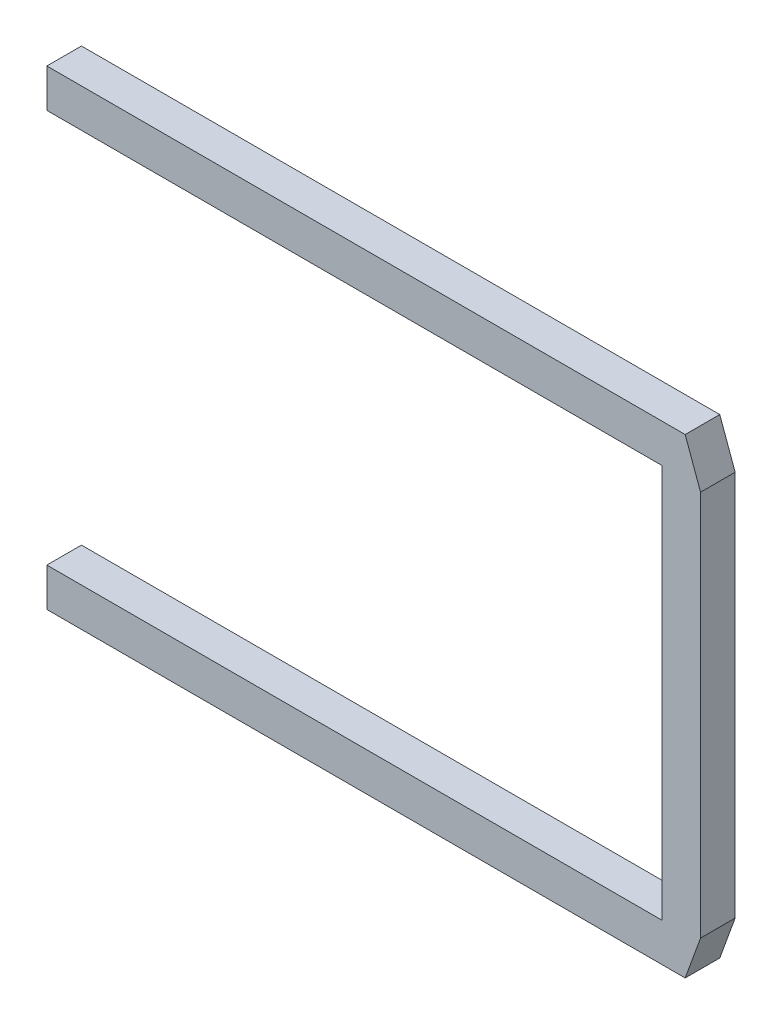
SolidWorks part; units mm, degrees
ref_plane "Front Plane" through (0, 0, 0) normal (0, 0, 1) x (1, 0, 0)
ref_plane "Top Plane" through (0, 0, 0) normal (0, 1, 0) x (1, 0, 0)
ref_plane "Right Plane" through (0, 0, 0) normal (1, 0, 0) x (0, 0, -1)
sketch "Sketch1" plane through (0, 0, 0) normal (0, 0, 1) x (1, 0, 0)
  line L0 (-42.5, -25.6) -> (-42.5, -30.6)
  line L1 (-42.5, 30.6) -> (42.5, 30.6)
  line L2 (-42.5, 30.6) -> (-42.5, 25.6)
  line L3 (-42.5, -30.6) -> (42.5, -30.6)
  line L4 (42.5, 30.6) -> (42.5, -30.6)
  line L5 (-42.5, 30.6) -> (42.5, -30.6) construction
  line L6 (-42.5, -30.6) -> (42.5, 30.6) construction
  line L7 (-42.5, 25.6) -> (37.5, 25.6)
  line L9 (-42.5, -25.6) -> (37.5, -25.6)
  line L10 (37.5, 25.6) -> (37.5, -25.6)
  point P0 (0, 0)
  dimension "D1" = 5
  dimension "D2" = 5
  dimension "D3" = 5
  dimension "D4" = 80
  dimension "D5" = 51.2
extrude "Boss-Extrude1" add sketch "Sketch1" along normal blind 4.5
chamfer "Chamfer1" distance 2 angle 70 2 edges at (42.5, -30.6, 2.25) (42.5, 30.6, 2.25)
